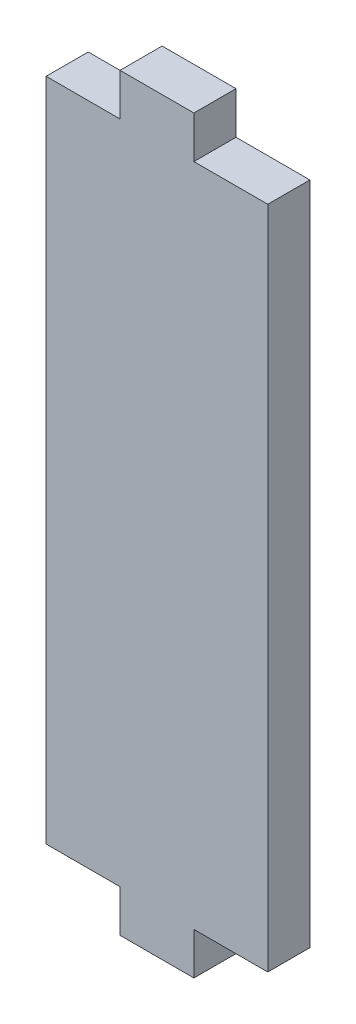
SolidWorks part; units mm, degrees
ref_plane "Front Plane" through (0, 0, 0) normal (0, 0, 1) x (1, 0, 0)
ref_plane "Top Plane" through (0, 0, 0) normal (0, 1, 0) x (1, 0, 0)
ref_plane "Right Plane" through (0, 0, 0) normal (1, 0, 0) x (0, 0, -1)
sketch "Sketch1" plane through (0, 0, 0) normal (0, 0, 1) x (1, 0, 0)
  line L1 (0, 0) -> (25.4, 0)
  line L2 (0, 0) -> (0, 85.852)
  line L3 (0, 85.852) -> (25.4, 85.852)
  line L4 (25.4, 0) -> (25.4, 85.852)
  dimension "D1" = 85.852
  dimension "D2" = 25.4
extrude "Boss-Extrude1" add sketch "Sketch1" along normal blind 4.826
sketch "Sketch2" plane through (0, 0, 4.826) normal (0, 0, 1) x (1, 0, 0)
  line L0 (0, 0) -> (25.4, 0) construction
  line L1 (0, 0) -> (8.4667, 0)
  line L2 (0, 0) -> (0, 4.826)
  line L3 (0, 4.826) -> (8.4667, 4.826)
  line L4 (8.4667, 0) -> (8.4667, 4.826)
  line L5 (8.4667, 4.826) -> (16.9333, 4.826) construction
  line L6 (0, 42.926) -> (25.4, 42.926) construction
  line L7 (0, 85.852) -> (0, 0) construction
  line L8 (8.4667, 81.026) -> (16.9333, 81.026) construction
  line L9 (25.4, 0) -> (25.4, 85.852) construction
  line L10 (16.9333, 0) -> (25.4, 0)
  line L11 (16.9333, 0) -> (16.9333, 4.826)
  line L12 (16.9333, 4.826) -> (25.4, 4.826)
  line L13 (25.4, 0) -> (25.4, 4.826)
  line L14 (25.4, 85.852) -> (25.4, 81.026)
  line L15 (16.9333, 81.026) -> (25.4, 81.026)
  line L16 (16.9333, 85.852) -> (16.9333, 81.026)
  line L17 (16.9333, 85.852) -> (25.4, 85.852)
  line L18 (8.4667, 85.852) -> (8.4667, 81.026)
  line L19 (0, 81.026) -> (8.4667, 81.026)
  line L20 (0, 85.852) -> (0, 81.026)
  line L21 (0, 85.852) -> (8.4667, 85.852)
  dimension "D1" = 4.826
extrude "Cut-Extrude1" cut sketch "Sketch2" against normal through all
equation "\"MDF\"= 0.19in"
equation "\"PVCID\" = 2.067in"
equation "\"PVCOD\" = 2.375in"
equation "\"GenDiameter\"= 60mm"
equation "\"GenCutDiameter\" = 1.8in"
equation "\"GenCutDistance\" = 1"
equation "\"TowerHeight\" = 6in"
equation "\"TowerFrontBase\" = 3in"
equation "\"FunnelHeight\" = 1in"
equation "\"FunnelAngle\" = 20"
equation "\"TowerSideBase\" = 3in"
equation "\"TowerPanelLength\" = 2in"
equation "\"TowerPanelLeeway\" = 0.5in"
equation "\"BaseLength\" = 9in"
equation "\"BaseWidth\" = 10in"
equation "\"WheelHoleLength\" = 3.25in"
equation "\"WheelHoleWidth\" = 26mm"
equation "\"WheelHoleFromBack\" = 1in"
equation "\"DropLength\" = 1in"
equation "\"DropWidth\" = 8.5in"
equation "\"BumperWidth\" = 1in"
equation "\"SmallHexDiameter\" = 0.185in"
equation "\"SmallHexHeight\" = 0.701in"
equation "\"ScrewSize\" = 0.106in"
equation "\"BigHexDiameter\" = 0.251in"
equation "\"BigHexHeight\" = 0.374in"
equation "\"PCBThickness\" = 0.066in"
equation "\"ConnectorHeight\" = 0.517in"
equation "\"BoardHeight\" = 0.583in"
equation "\"UnoStackHeight\" = 1.351in"
equation "\"UnoStackWidth\" = 3.053in"
equation "\"UnoStackLength\" = 3.152in"
equation "\"HBridgeWidth\" = 1.797in"
equation "\"HBridgeLength\" = 2.236in"
equation "\"DSWidth\" = 1.820in"
equation "\"DSLength\" = 1.833in"
equation "\"StepperWidth\" = 1.799in"
equation "\"StepperLength\" = 2.248in"
equation "\"ULNWidth\" = 1.304in"
equation "\"ULNLength\" = 1.545in"
equation "\"VSwitchHeight\" = 0.392in"
equation "\"VSwitchWidth\" = 0.637in"
equation "\"VSwitchLength\" = 1.097in"
equation "\"SkateWheelDiameter\" = 80mm"
equation "\"SkateWheelThickness\" = 24mm"
equation "\"BaseDistance\" = 3in"
equation "\"DummyVar\" = 2in"
equation "\"D1@Sketch1\"=2*\"MDF\"+3in"
equation "\"D1@Boss-Extrude1\"=\"MDF\""
equation "\"D1@Sketch2\"=\"MDF\""
